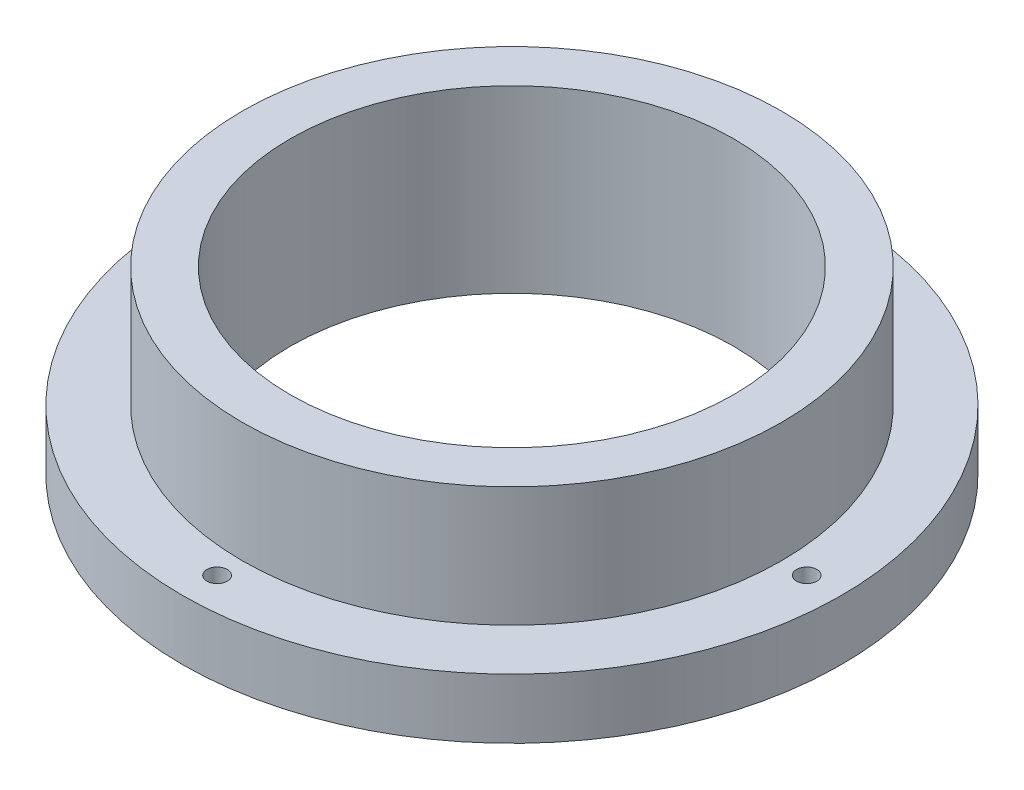
SolidWorks part; units mm, degrees
ref_plane "前视" through (0, 0, 0) normal (0, 0, 1) x (1, 0, 0)
ref_plane "上视" through (0, 0, 0) normal (0, 1, 0) x (1, 0, 0)
ref_plane "右视" through (0, 0, 0) normal (1, 0, 0) x (0, 0, -1)
sketch "草图2" plane through (0, 0, 0) normal (0, 1, 0) x (1, 0, 0)
  line L0 (0, 30.9145) -> (0, -31.6347) construction
  line L1 (-32.2104, 0) -> (35.7149, 0) construction
  circle A0 centre (0, 0) radius 27.5
  circle A1 centre (0, 0) radius 24.6 construction
  circle A2 centre (0, 24.6) radius 0.85
  circle A3 centre (24.6, 0) radius 0.85
  circle A4 centre (0, -24.6) radius 0.85
  circle A5 centre (-24.6, 0) radius 0.85
  point P19 (0, 0)
  dimension "D1" = 55
  dimension "D2" = 49.2
  dimension "D3" = 1.7
  dimension "D4" = 4
extrude "凸台-拉伸1" add sketch "草图2" along normal blind 5
sketch "草图3" plane through (0, 5, 0) normal (0, 1, 0) x (1, 0, 0)
  circle A0 centre (0, 0) radius 22.5
  dimension "D1" = 45
extrude "凸台-拉伸2" add sketch "草图3" along normal blind 10
sketch "草图4" plane through (0, 15, 0) normal (0, 1, 0) x (1, 0, 0)
  circle A0 centre (0, 0) radius 18.5
  circle A1 centre (0, 0) radius 22.5 construction
  dimension "D1" = 4
extrude "切除-拉伸1" cut sketch "草图4" against normal through all
